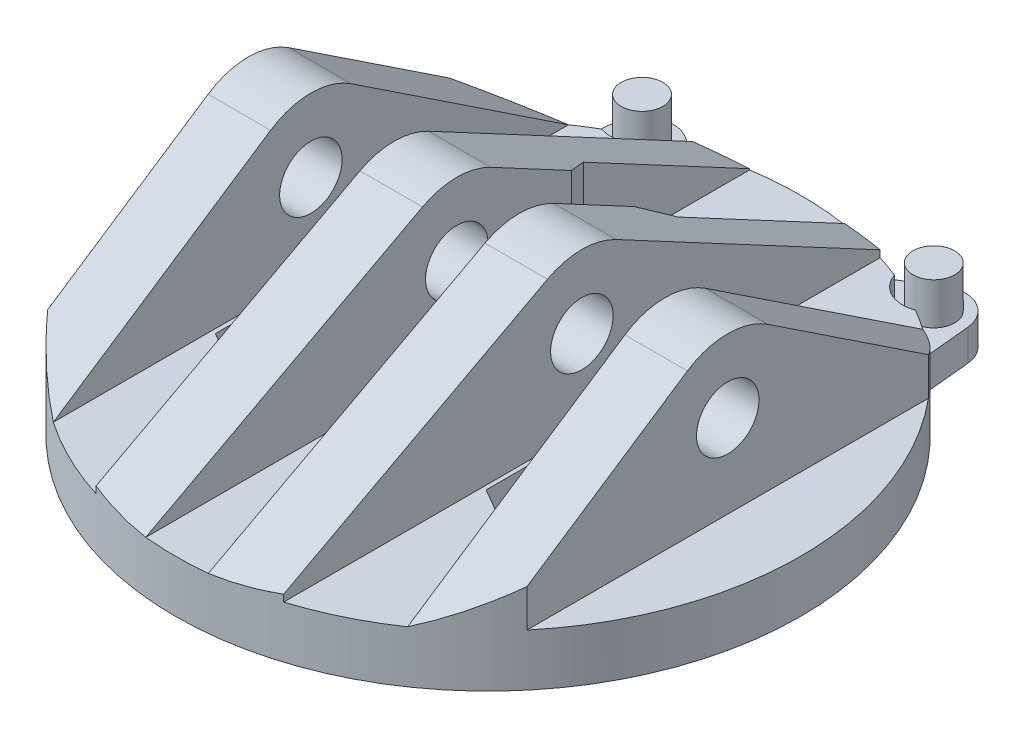
SolidWorks part; units mm, degrees
ref_plane "Front Plane" through (0, 0, 0) normal (0, 0, 1) x (1, 0, 0)
ref_plane "Top Plane" through (0, 0, 0) normal (0, 1, 0) x (1, 0, 0)
ref_plane "Right Plane" through (0, 0, 0) normal (1, 0, 0) x (0, 0, -1)
sketch "Sketch1" plane through (0, 0, 0) normal (0, 1, 0) x (1, 0, 0)
  line L0 (0, 0) -> (0, 15) construction
  line L1 (0, 0) -> (12.9904, -7.5) construction
  line L2 (0, 0) -> (-12.9904, -7.5) construction
  circle A0 centre (0, 0) radius 30
  circle A1 centre (0, 0) radius 15 construction
  circle A2 centre (0, 15) radius 2.1
  circle A3 centre (12.9904, -7.5) radius 2.1
  circle A4 centre (-12.9904, -7.5) radius 2.1
  dimension "D1" = 60
  dimension "D2" = 30
  dimension "D5" = 4.2
  dimension "D3" = 120
  dimension "D4" = 120
extrude "Boss-Extrude1" add sketch "Sketch1" along normal blind 5
sketch "Sketch2" plane through (0, 5, 0) normal (0, 1, 0) x (1, 0, 0)
  line L0 (0, 30) -> (0, -30) construction
  line L5 (17, 11) -> (17, 24.7184)
  line L6 (-3, -29.8496) -> (3, -29.8496)
  line L8 (4.1569, 15) -> (2.0785, 18.6)
  line L9 (2.0785, 18.6) -> (-2.0785, 18.6)
  line L10 (-2.0785, 18.6) -> (-4.1569, 15)
  line L11 (-4.1569, 15) -> (-2.0785, 11.4)
  line L12 (-2.0785, 11.4) -> (2.0785, 11.4)
  line L13 (2.0785, 11.4) -> (4.1569, 15)
  line L14 (-12.9904, -3.3431) -> (-16.5904, -5.4215)
  line L15 (-16.5904, -5.4215) -> (-16.5904, -9.5785)
  line L16 (-16.5904, -9.5785) -> (-12.9904, -11.6569)
  line L17 (-12.9904, -11.6569) -> (-9.3904, -9.5785)
  line L18 (-9.3904, -9.5785) -> (-9.3904, -5.4215)
  line L19 (-9.3904, -5.4215) -> (-12.9904, -3.3431)
  line L20 (12.9904, -3.3431) -> (9.3904, -5.4215)
  line L21 (9.3904, -5.4215) -> (9.3904, -9.5785)
  line L22 (9.3904, -9.5785) -> (12.9904, -11.6569)
  line L23 (12.9904, -11.6569) -> (16.5904, -9.5785)
  line L24 (16.5904, -9.5785) -> (16.5904, -5.4215)
  line L25 (16.5904, -5.4215) -> (12.9904, -3.3431)
  line L49 (-3, -29.8496) -> (-3, 11)
  line L50 (-3, 11) -> (3, 11)
  line L51 (3, -29.8496) -> (3, 11)
  line L52 (-3, -29.8496) -> (3, 11) construction
  line L53 (-3, 11) -> (3, -29.8496) construction
  line L54 (3, 11) -> (9, 11)
  line L55 (3, 11) -> (3, -28.6182)
  line L56 (3, -28.6182) -> (9, -28.6182)
  line L57 (9, 11) -> (9, -28.6182)
  line L58 (9, 11) -> (17, 11)
  line L59 (9, 11) -> (9, -24.7184)
  line L60 (9, -24.7184) -> (17, -24.7184)
  line L61 (17, 11) -> (17, -24.7184)
  line L62 (17, 19.2614) -> (23, 19.2614)
  line L63 (17, 19.2614) -> (17, -19.2614)
  line L64 (17, -19.2614) -> (23, -19.2614)
  line L65 (23, 19.2614) -> (23, -19.2614)
  line L66 (4.5569, 11) -> (4.5569, 29.6519)
  line L67 (9, 11) -> (9, 28.6182)
  line L68 (3, 11) -> (4.5569, 13.6967)
  circle A1 centre (0, 0) radius 30 construction
  circle A2 centre (0, 15) radius 3.6 construction
  circle A3 centre (-12.9904, -7.5) radius 3.6 construction
  circle A4 centre (12.9904, -7.5) radius 3.6 construction
  circle A5 centre (0, 0) radius 30
  circle A6 centre (0, 0) radius 30
  point P2 (0, -9.4248)
  point P8 (0, -9.4248)
  circle M7 centre (0, 0) radius 30
  dimension "D1" = 6
  dimension "D2" = 0.4
  dimension "D3" = 6
  dimension "D4" = 7.2
  dimension "D5" = 8
  dimension "D6" = 6
  dimension "D7" = 0
  dimension "D8" = 0.4
sketch "Sketch7" plane through (0, 5, 0) normal (0, 1, 0) x (1, 0, 0)
  line L1 (0, 19.1569) -> (-3.6, 17.0785)
  line L2 (-3.6, 17.0785) -> (-3.6, 12.9215)
  line L3 (-3.6, 12.9215) -> (0, 10.8431)
  line L4 (0, 10.8431) -> (3.6, 12.9215)
  line L5 (3.6, 12.9215) -> (3.6, 17.0785)
  line L6 (3.6, 17.0785) -> (0, 19.1569)
  line L7 (12.9904, -3.3431) -> (9.3904, -5.4215)
  line L8 (9.3904, -5.4215) -> (9.3904, -9.5785)
  line L9 (9.3904, -9.5785) -> (12.9904, -11.6569)
  line L10 (12.9904, -11.6569) -> (16.5904, -9.5785)
  line L11 (16.5904, -9.5785) -> (16.5904, -5.4215)
  line L12 (16.5904, -5.4215) -> (12.9904, -3.3431)
  line L13 (-12.9904, -3.3431) -> (-16.5904, -5.4215)
  line L14 (-16.5904, -5.4215) -> (-16.5904, -9.5785)
  line L15 (-16.5904, -9.5785) -> (-12.9904, -11.6569)
  line L16 (-12.9904, -11.6569) -> (-9.3904, -9.5785)
  line L17 (-9.3904, -9.5785) -> (-9.3904, -5.4215)
  line L18 (-9.3904, -5.4215) -> (-12.9904, -3.3431)
  circle A0 centre (0, 15) radius 3.6 construction
  circle A1 centre (12.9904, -7.5) radius 3.6 construction
  circle A2 centre (-12.9904, -7.5) radius 3.6 construction
  dimension "D1" = 7.2
extrude "Cut-Extrude2" cut sketch "Sketch7" against normal blind 2
extrude "Boss-Extrude5" add sketch "Sketch2" along normal blind 15 contours L57 L54 L51 L56 | L56 L51 M7 | L64 L61 M7 | L65 L62 L61 L64 | L61 L62 L5 M7 | L54 L67 L66 M7 | L68 L54 L66
sketch "Sketch8" plane through (23, 0, 0) normal (1, 0, 0) x (0, 0, -1)
  line L0 (0, 20) -> (0, 5) construction
  line L1 (19.2614, 20) -> (-19.2614, 20) construction
  line L2 (19.2614, 5) -> (-19.2614, 5) construction
  circle A0 centre (0, 13) radius 3
  point P8 (0, 16)
  dimension "D1" = 6
  dimension "D2" = 4
extrude "Cut-Extrude3" cut sketch "Sketch8" against normal through all
sketch "Sketch9" plane through (3, 0, 0) normal (-1, 0, 0) x (0, 0, 1)
  line L0 (0, 20) -> (0, 5) construction
  line L1 (-29.8496, 5) -> (-3.2966, 19.1752)
  line L3 (29.8496, 20) -> (-11, 20) construction
  line L4 (29.8496, 5) -> (-11, 5) construction
  line L6 (29.8496, 5) -> (3.2966, 19.1752)
  line L8 (-13.6967, 5) -> (-11, 5) construction
  line L10 (-11, 20) -> (-13.6967, 20) construction
  line L11 (-29.6519, 5) -> (-13.6967, 5) construction
  line L12 (-13.6967, 20) -> (-29.6519, 20) construction
  line L13 (-29.6519, 20) -> (-29.6519, 5) construction
  line L14 (-11, 5) -> (29.8496, 5) construction
  line L15 (29.8496, 5) -> (29.8496, 20) construction
  line L16 (-13.6967, 5) -> (-11, 5)
  line L17 (-11, 20) -> (-13.6967, 20)
  line L18 (-29.6519, 5) -> (-13.6967, 5)
  line L19 (-13.6967, 20) -> (-29.6519, 20)
  line L20 (-29.6519, 20) -> (-29.6519, 5)
  line L21 (-11, 5) -> (29.8496, 5)
  line L22 (29.8496, 5) -> (29.8496, 20)
  line L23 (29.8496, 20) -> (-11, 20)
  circle A0 centre (0, 13) radius 3 construction
  circle A1 centre (0, 13) radius 3
  arc A2 (-3.2966, 19.1752) -> (3.2966, 19.1752) centre (0, 13) cw
  line M15 (29.8496, 5) -> (29.8496, 20)
  line M16 (29.8496, 20) -> (-11, 20)
  line M17 (-11, 20) -> (-11, 5)
extrude "Cut-Extrude4" cut sketch "Sketch9" against normal up to next contours L19 L20 L1 L17 M17 | L1 A2 L23 M17 | A2 L6 M16 M15
sketch "Sketch10" plane through (17, 0, 0) normal (-1, 0, 0) x (0, 0, 1)
  line L0 (0, 5.0953) -> (0, 20) construction
  line L2 (24.7184, 5) -> (3.8701, 18.8329)
  line L3 (-24.7184, 5) -> (-3.8701, 18.8329)
  line L6 (-24.7184, 5) -> (24.7184, 5)
  line L7 (24.7184, 5) -> (24.7184, 20)
  line L8 (24.7184, 20) -> (-24.7184, 20)
  line L9 (-24.7184, 20) -> (-24.7184, 5)
  line L10 (-24.7184, 5) -> (24.7184, 5)
  line L11 (24.7184, 5) -> (24.7184, 20)
  line L12 (24.7184, 20) -> (-24.7184, 20)
  line L13 (-24.7184, 20) -> (-24.7184, 5)
  circle A0 centre (0, 13) radius 3 construction
  circle A1 centre (0, 13) radius 3
  arc A2 (-3.8701, 18.8329) -> (3.8701, 18.8329) centre (0, 13) cw
  line M10 (24.7184, 5) -> (24.7184, 20)
  line M11 (24.7184, 20) -> (-24.7184, 20)
  line M12 (-24.7184, 20) -> (-24.7184, 5)
  dimension "D1" = 0
extrude "Cut-Extrude5" cut sketch "Sketch10" against normal up to next contours L3 A2 L12 M12 | A2 L2 M11 M10
ref_plane "Plane1" through (0, 0, 0) normal (-1, 0, 0) x (0, 0, 1)
mirror "Mirror1" about plane through (0, 0, 0) normal (-1, 0, 0) of "Cut-Extrude5", "Cut-Extrude4", "Cut-Extrude3", "Boss-Extrude5"
sketch "Sketch13" plane through (0, 0, 0) normal (0, -1, 0) x (1, 0, 0)
  line L0 (0, 0) -> (18.2639, -37.5389) construction
  line L1 (0, 0) -> (0, -39.0213) construction
  line L2 (16.986, -29.0648) -> (17.4375, -24.4117)
  line L3 (12.3851, -31.3032) -> (8.4453, -28.7867)
  line L4 (14, -28.775) -> (0, -28.775) construction
  arc A0 (12.3851, -31.3032) -> (16.986, -29.0648) centre (14, -28.775) ccw
  circle A1 centre (0, 0) radius 30 construction
  circle A3 centre (0, 0) radius 30
  circle A4 centre (0, 0) radius 30
  point P13 (15.3125, -31.4726)
  circle M1 centre (0, 0) radius 30
  dimension "D2" = 3
  dimension "D1" = 14
  dimension "D3" = 10
  dimension "D5" = 35
  dimension "D4" = 0
extrude "Boss-Extrude8" add sketch "Sketch13" against normal blind 3 contours L3 A0 L2 M1
sketch "Sketch15" plane through (0, 5, 0) normal (0, 1, 0) x (1, 0, 0)
  line L2 (9, 28.6182) -> (9, -28.6182)
  line L3 (17, -24.7184) -> (17, 24.7184)
  line L4 (9, 28.6182) -> (9, -28.6182)
  line L5 (17, -24.7184) -> (17, 24.7184)
  circle A0 centre (14, 28.775) radius 3
  arc A3 (9, -28.6182) -> (17, -24.7184) centre (0, 0) ccw
  arc A4 (17, 24.7184) -> (9, 28.6182) centre (0, 0) ccw
  arc A5 (9, -28.6182) -> (17, -24.7184) centre (0, 0) ccw
  arc A6 (17, 24.7184) -> (9, 28.6182) centre (0, 0) ccw
  arc M5 (17, 24.7184) -> (9, 28.6182) centre (0, 0) ccw
  dimension "D1" = 0
extrude "Cut-Extrude8" cut sketch "Sketch15" against normal up to surface (2 mm away) contours A0 M5 up to face at (14.0161, 3, -28.8081)
sketch "Sketch14" plane through (0, 3, 0) normal (0, 1, 0) x (1, 0, 0)
  line L2 (12.3851, 31.3032) -> (8.4453, 28.7867)
  line L3 (17.4375, 24.4117) -> (16.986, 29.0648)
  line L4 (12.3851, 31.3032) -> (8.4453, 28.7867)
  line L5 (17.4375, 24.4117) -> (16.986, 29.0648)
  circle A0 centre (14, 28.775) radius 2
  arc A2 (11.1452, 27.8529) -> (8.4453, 28.7867) centre (0, 0) ccw
  arc A3 (16.986, 29.0648) -> (12.3851, 31.3032) centre (14, 28.775) ccw
  arc A4 (11.1452, 27.8529) -> (8.4453, 28.7867) centre (0, 0) ccw
  arc A5 (16.986, 29.0648) -> (12.3851, 31.3032) centre (14, 28.775) ccw
  arc A9 (11.1452, 27.8529) -> (15.0364, 25.9597) centre (14, 28.775) ccw
  arc A10 (11.1452, 27.8529) -> (15.0364, 25.9597) centre (14, 28.775) ccw
  arc A11 (17.4375, 24.4117) -> (15.0364, 25.9597) centre (0, 0) ccw
  arc A12 (17.4375, 24.4117) -> (15.0364, 25.9597) centre (0, 0) ccw
  dimension "3.8" = 4
  dimension "D1" = 0
extrude "Boss-Extrude9" add sketch "Sketch14" along normal blind 4 contours A0
mirror "Mirror2" about plane through (0, 0, 0) normal (-1, 0, 0) of "Cut-Extrude8", "Boss-Extrude9", "Boss-Extrude8"
